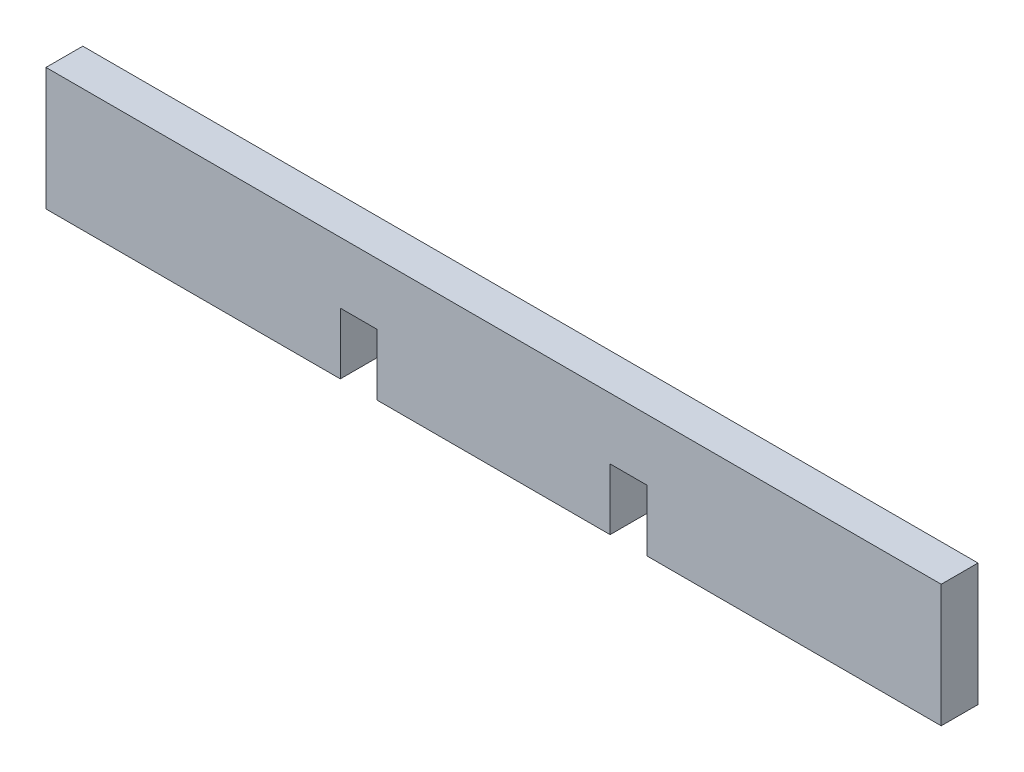
SolidWorks part; units mm, degrees
material "Acrylic (Medium-high impact)"
ref_plane "Front Plane" through (0, 0, 0) normal (0, 0, 1) x (1, 0, 0)
ref_plane "Top Plane" through (0, 0, 0) normal (0, 1, 0) x (1, 0, 0)
ref_plane "Right Plane" through (0, 0, 0) normal (1, 0, 0) x (0, 0, -1)
sketch "Sketch1" plane through (0, 0, 0) normal (0, 0, 1) x (1, 0, 0)
  line L0 (-4.0923, 0) -> (5.85, 0)
  line L1 (5.85, 0) -> (5.85, 5)
  line L2 (5.85, 5) -> (8.85, 5)
  line L3 (8.85, 5) -> (8.85, 0)
  line L4 (8.85, 0) -> (32.85, 0)
  line L5 (32.85, 0) -> (32.85, 10)
  line L6 (32.85, 10) -> (-40.15, 10)
  line L7 (-40.15, 10) -> (-40.15, 0)
  line L8 (-40.15, 0) -> (-16.15, 0)
  line L9 (-16.15, 0) -> (-16.15, 5)
  line L10 (-16.15, 5) -> (-13.15, 5)
  line L11 (-13.15, 5) -> (-13.15, 0)
  line L12 (-13.15, 0) -> (-4.0923, 0)
  dimension "D1" = 19
  dimension "D2" = 24
  dimension "D3" = 24
  dimension "D4" = 3
  dimension "D5" = 3
  dimension "D6" = 5
  dimension "D7" = 5
  dimension "D8" = 10
extrude "Boss-Extrude1" add sketch "Sketch1" along normal blind 3
